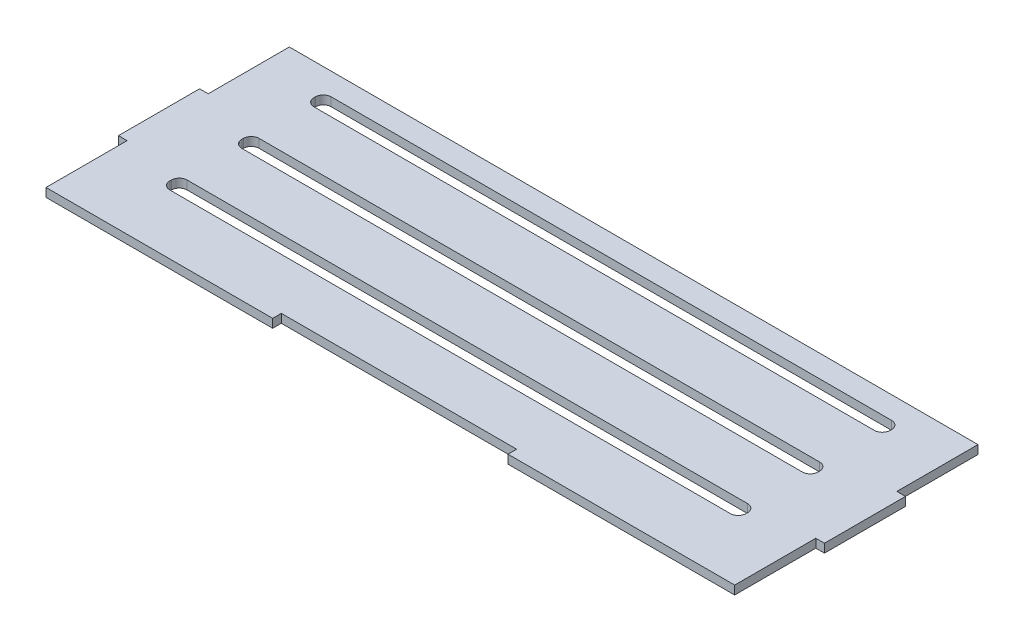
SolidWorks part; units mm, degrees
ref_plane "Front Plane" through (0, 0, 0) normal (0, 0, 1) x (1, 0, 0)
ref_plane "Top Plane" through (0, 0, 0) normal (0, 1, 0) x (1, 0, 0)
ref_plane "Right Plane" through (0, 0, 0) normal (1, 0, 0) x (0, 0, -1)
sketch "Sketch1" plane through (0, 0, 0) normal (0, 1, 0) x (1, 0, 0)
  line L1 (0, 0) -> (490, 0)
  line L2 (0, 0) -> (0, 168.89)
  line L3 (0, 168.89) -> (490, 168.89)
  line L4 (490, 0) -> (490, 168.89)
  dimension "D1" = 490
  dimension "D2" = 168.89
extrude "Boss-Extrude1" add sketch "Sketch1" along normal blind 6
sketch "Sketch2" plane through (0, 6, 0) normal (0, 1, 0) x (1, 0, 0)
  line L0 (490, 0) -> (490, 168.89) construction
  line L5 (0, 0) -> (490, 0) construction
  line L6 (163.3333, 0) -> (326.6667, 0)
  line L7 (163.3333, 0) -> (163.3333, 6)
  line L8 (163.3333, 6) -> (326.6667, 6)
  line L9 (326.6667, 0) -> (326.6667, 6)
  line L10 (0, 168.89) -> (0, 0) construction
  point P0 (245, 6)
  dimension "D1" = 6
  dimension "D2" = 245
  dimension "D3" = 163.3333
  dimension "D4" = 163.3333
extrude "Cut-Extrude1" cut sketch "Sketch2" against normal through all
sketch "Sketch4" plane through (0, 6, 0) normal (0, 1, 0) x (1, 0, 0)
  line L1 (0, 168.89) -> (6, 168.89)
  line L2 (0, 168.89) -> (0, 112.5933)
  line L3 (0, 112.5933) -> (6, 112.5933)
  line L4 (6, 168.89) -> (6, 112.5933)
  line L5 (0, 0) -> (6, 0)
  line L6 (0, 0) -> (0, 56.2967)
  line L7 (0, 56.2967) -> (6, 56.2967)
  line L8 (6, 0) -> (6, 56.2967)
  line L9 (490, 0) -> (484, 0)
  line L10 (490, 0) -> (490, 56.2967)
  line L11 (490, 56.2967) -> (484, 56.2967)
  line L12 (484, 0) -> (484, 56.2967)
  line L13 (490, 168.89) -> (484, 168.89)
  line L14 (490, 168.89) -> (490, 112.5933)
  line L15 (490, 112.5933) -> (484, 112.5933)
  line L16 (484, 168.89) -> (484, 112.5933)
  dimension "D1" = 6
  dimension "D2" = 56.2967
extrude "Cut-Extrude3" cut sketch "Sketch4" against normal through all
sketch "Sketch5" plane through (0, 6, 0) normal (0, 1, 0) x (1, 0, 0)
  line L0 (484, 168.89) -> (484, 112.5933) construction
  line L1 (50.5, 153.4495) -> (439.5, 153.4495)
  line L2 (45, 147.9495) -> (45, 146.9495)
  line L3 (50.5, 141.4495) -> (439.5, 141.4495)
  line L4 (445, 147.9495) -> (445, 146.9495)
  line L6 (6, 112.5933) -> (6, 168.89) construction
  arc A0 (439.5, 141.4495) -> (445, 146.9495) centre (439.5, 146.9495) ccw
  arc A1 (439.5, 153.4495) -> (445, 147.9495) centre (439.5, 147.9495) cw
  arc A2 (45, 146.9495) -> (50.5, 141.4495) centre (50.5, 146.9495) ccw
  arc A3 (50.5, 153.4495) -> (45, 147.9495) centre (50.5, 147.9495) ccw
  point P11 (445, 153.4495)
  point P14 (45, 141.4495)
  point P17 (45, 153.4495)
  dimension "D4" = 5.5
  dimension "D1" = 400
  dimension "D2" = 39
  dimension "D3" = 12
  dimension "D5" = 39
extrude "Cut-Extrude4" cut sketch "Sketch5" against normal through all
pattern_linear "LPattern1" count 3 spacing 50 along (0, 0, 1) of "Cut-Extrude4"
